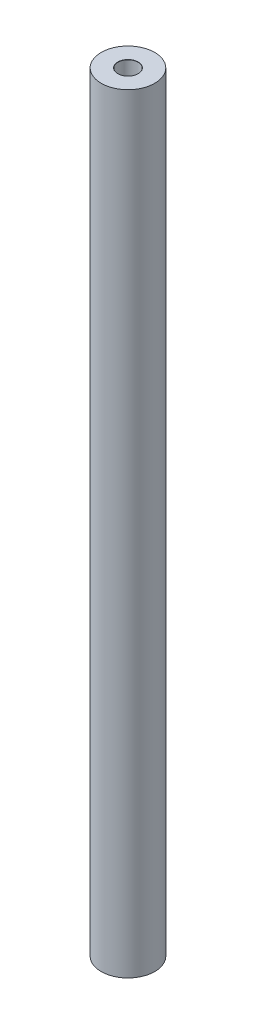
SolidWorks part; units mm, degrees
ref_plane "Front Plane" through (0, 0, 0) normal (0, 0, 1) x (1, 0, 0)
ref_plane "Top Plane" through (0, 0, 0) normal (0, 1, 0) x (1, 0, 0)
ref_plane "Right Plane" through (0, 0, 0) normal (1, 0, 0) x (0, 0, -1)
sketch "Sketch2" plane through (0, 0, 0) normal (0, 1, 0) x (1, 0, 0)
  circle A0 centre (0, 0) radius 4
  dimension "D1" = 8
extrude "Boss-Extrude1" add sketch "Sketch2" along normal blind 115
sketch "Sketch3" plane through (0, 115, 0) normal (0, 1, 0) x (1, 0, 0)
  point P0 (0, 0)
hole_wizard "Ø3.0mm Dowel Hole1" positions "Sketch3" profile "Sketch5" hole size "Ø3.0" standard "AS"
sketch "Sketch5" plane through (0, 115, 0) normal (1, 0, 0) x (0, 0, 1)
  line L0 (0, 0) -> (0, 15.9013)
  line L1 (0, 15.9013) -> (1.5, 15)
  line L2 (1.5, 15) -> (1.5, 0.025)
  line L3 (1.5, 0.025) -> (1.525, 0)
  line L5 (1.525, 0) -> (0, 0)
  line L6 (-1.5, 0.025) -> (-1.525, 0) construction
  line L10 (0, 15.9013) -> (-1.5, 15) construction
  line L11 (0, -6.35) -> (0, 107.95) construction
  dimension "Hole Dia." = 3
  dimension "Hole Depth" = 15
  dimension "Near C'Sink Dia." = 3.05
  dimension "Near C'Sink Angle" = 90
  dimension "Drill Angle" = 118
ref_plane "Plane1" through (0, 57.5, 0) normal (0, 1, 0) x (1, 0, 0)
mirror "Mirror1" about plane through (0, 57.5, 0) normal (0, 1, 0) of "Ø3.0mm Dowel Hole1"
